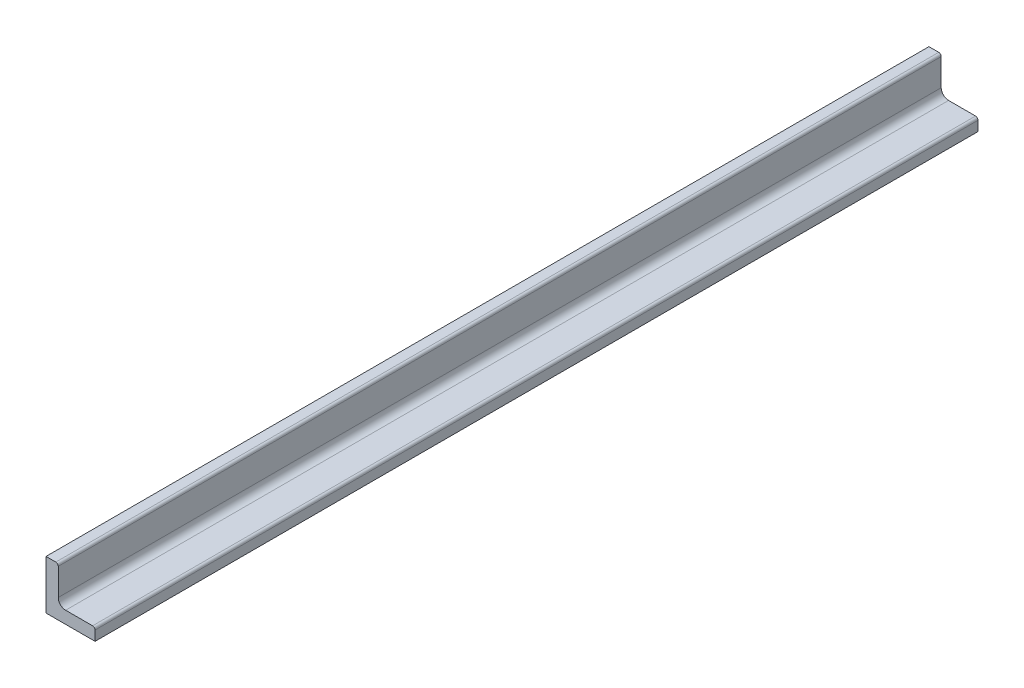
SolidWorks part; units mm, degrees
ref_plane "Front" through (0, 0, 0) normal (0, 0, 1) x (1, 0, 0)
ref_plane "Top" through (0, 0, 0) normal (0, 1, 0) x (1, 0, 0)
ref_plane "Right" through (0, 0, 0) normal (1, 0, 0) x (0, 0, -1)
sketch "Sketch1" plane through (0, 0, 0) normal (0, 0, 1) x (1, 0, 0)
  line L0 (0, 0) -> (0, 9.525)
  line L1 (0, 9.525) -> (-3.175, 9.525)
  line L2 (-3.175, 9.525) -> (-3.175, -3.175)
  line L3 (-3.175, -3.175) -> (9.525, -3.175)
  line L4 (9.525, -3.175) -> (9.525, 0)
  line L5 (9.525, 0) -> (0, 0)
  dimension "Height" = 12.7
  dimension "Width" = 12.7
  dimension "Wall Thickness" = 3.175
sketch "Sketch2" plane through (0, 0, 0) normal (1, 0, 0) x (0, 0, -1)
  line L0 (-457.2, 0) -> (457.2, 0) construction
  point P2 (0, 0)
  dimension "Length" = 914.4
sketch "Sketch3" plane through (0, 0, 0) normal (0, 0, 1) x (1, 0, 0)
  line L0 (0, 0) -> (0, 9.525) construction
  line L1 (0, 9.525) -> (-3.175, 9.525) construction
  line L2 (-3.175, 9.525) -> (-3.175, -3.175) construction
  line L3 (-3.175, -3.175) -> (9.525, -3.175) construction
  line L4 (9.525, -3.175) -> (9.525, 0) construction
  line L5 (9.525, 0) -> (0, 0) construction
  line L6 (0, 1.905) -> (0, 8.89)
  line L7 (-0.635, 9.525) -> (-3.175, 9.525)
  line L8 (-3.175, 9.525) -> (-3.175, -3.048)
  line L9 (-3.048, -3.175) -> (9.525, -3.175)
  line L10 (9.525, -3.175) -> (9.525, -0.635)
  line L11 (8.89, 0) -> (1.905, 0)
  arc A0 (0, 1.905) -> (1.905, 0) centre (1.905, 1.905) ccw
  arc A1 (9.525, -0.635) -> (8.89, 0) centre (8.89, -0.635) ccw
  arc A2 (0, 8.89) -> (-0.635, 9.525) centre (-0.635, 8.89) ccw
  arc A3 (-3.175, -3.048) -> (-3.048, -3.175) centre (-3.048, -3.048) ccw
  dimension "D1" = 1.905
  dimension "D2" = 0.127
  dimension "D3" = 0.635
extrude "Boss-Extrude1" add sketch "Sketch3" along normal blind 228.6
equation "\"D1@Sketch3\"=\"Height@Sketch1\"*.15"
equation "\"D2@Sketch3\"=\"Height@Sketch1\"*.01"
equation "\"D3@Sketch3\"=\"Height@Sketch1\"*.05"
